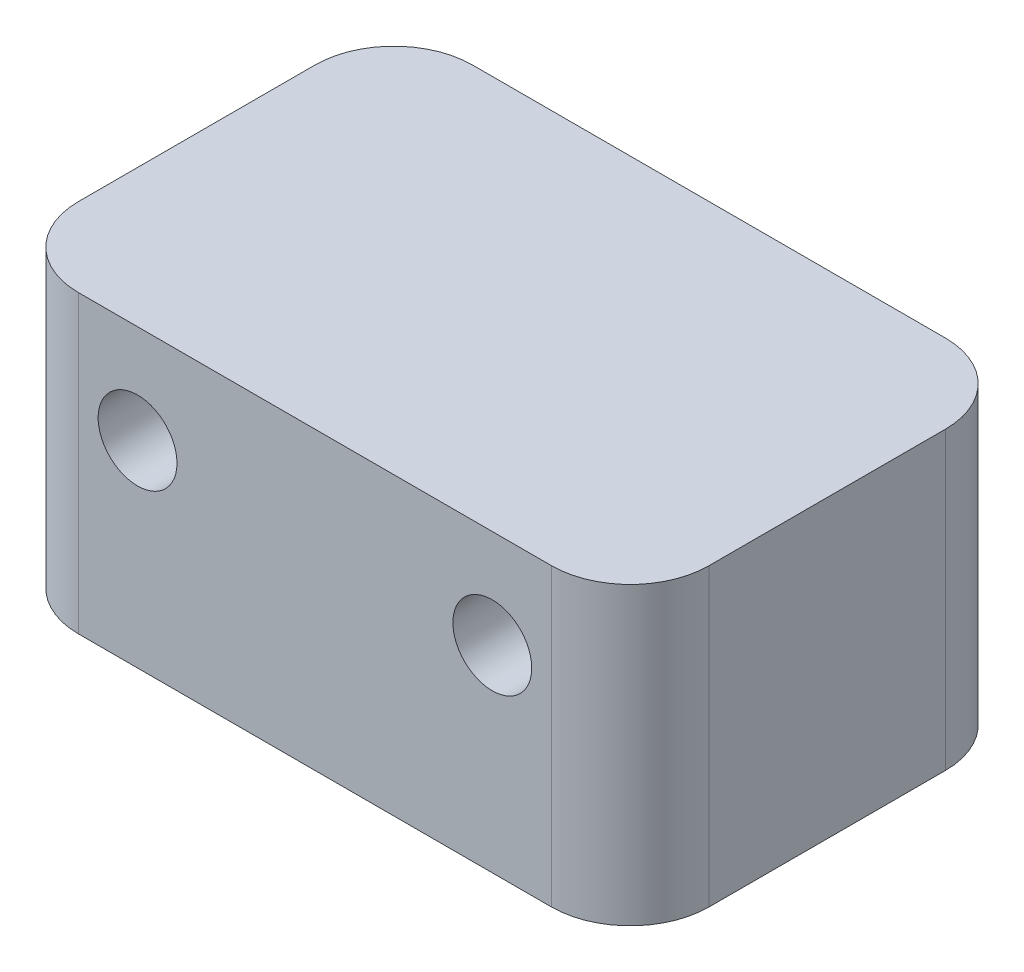
SolidWorks part; units mm, degrees
ref_plane "Plan de face" through (0, 0, 0) normal (0, 0, 1) x (1, 0, 0)
ref_plane "Plan de dessus" through (0, 0, 0) normal (0, 1, 0) x (1, 0, 0)
ref_plane "Plan de droite" through (0, 0, 0) normal (1, 0, 0) x (0, 0, -1)
sketch "Esquisse1" plane through (0, 0, 0) normal (0, 1, 0) x (1, 0, 0)
  line L0 (0, 0) -> (16, 0)
  line L1 (0, 0) -> (-16, 0)
  line L2 (-16, 0) -> (-16, 20)
  line L3 (-16, 20) -> (16, 20)
  line L4 (16, 20) -> (16, 0)
  dimension "D1" = 16
  dimension "D2" = 20
  dimension "D3" = 32
extrude "Boss.-Extru.1" add sketch "Esquisse1" along normal blind 15
fillet "Congé1" radius 4 4 edges at (-16, 7.5, -20) (16, 7.5, -20) (-16, 7.5, 0) (16, 7.5, 0)
sketch "Esquisse2" plane through (0, 0, 0) normal (0, -1, 0) x (1, 0, 0)
  line L0 (0, -20) -> (0, -10) construction
  line L1 (12, -20) -> (-12, -20) construction
  line L2 (0, -15) -> (-10, -15) construction
  line L3 (0, -15) -> (10, -15) construction
  line L4 (0, 0) -> (0, -5) construction
  circle A0 centre (-10, -15) radius 2
  circle A1 centre (10, -15) radius 2
  circle A2 centre (0, -5) radius 2
  dimension "D1" = 10
  dimension "D2" = 10
extrude "Enlèv. mat.-Extru.1" cut sketch "Esquisse2" against normal blind 12
sketch "Esquisse3" plane through (0, 0, 0) normal (0, 0, 1) x (1, 0, 0)
  line L0 (0, 0) -> (0, 10) construction
  line L1 (0, 10) -> (-9, 10) construction
  line L2 (0, 10) -> (9, 10) construction
  circle A0 centre (-9, 10) radius 2
  circle A1 centre (9, 10) radius 2
  dimension "D1" = 10
  dimension "D2" = 9
  dimension "D3" = 9
extrude "Enlèv. mat.-Extru.2" cut sketch "Esquisse3" against normal blind 12
